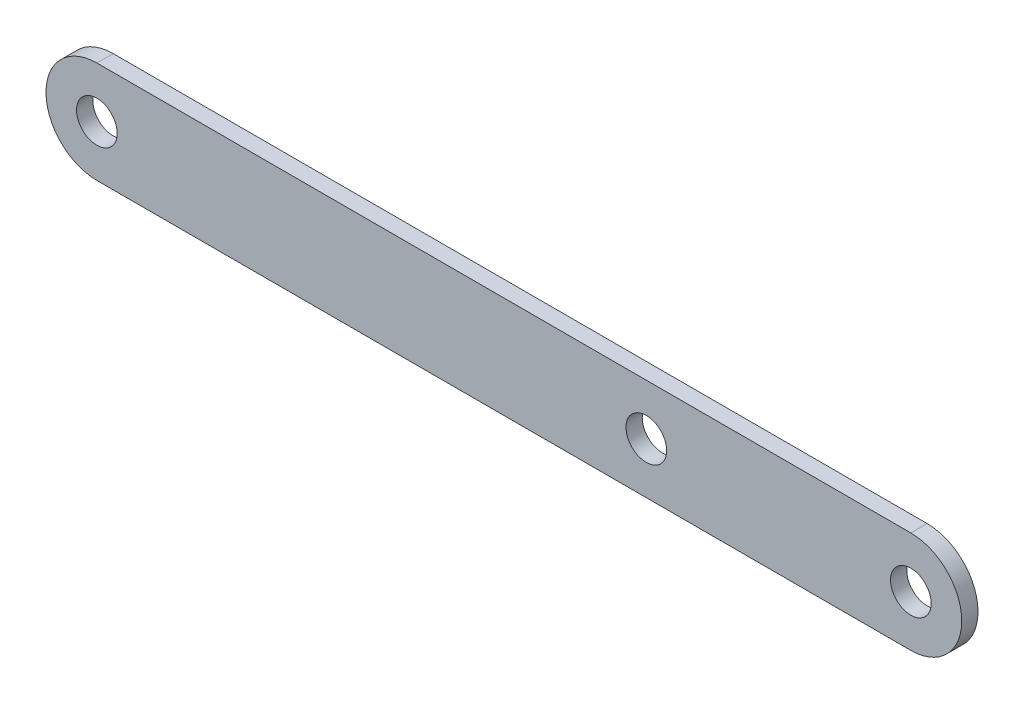
SolidWorks part; units mm, degrees
ref_plane "Plan de face" through (0, 0, 0) normal (0, 0, 1) x (1, 0, 0)
ref_plane "Plan de dessus" through (0, 0, 0) normal (0, 1, 0) x (1, 0, 0)
ref_plane "Plan de droite" through (0, 0, 0) normal (1, 0, 0) x (0, 0, -1)
sketch "Esquisse1" plane through (0, 0, 0) normal (0, 0, 1) x (1, 0, 0)
  line L0 (-200, 0) -> (200, 0) construction
  line L1 (-200, 25) -> (200, 25)
  line L2 (-200, -25) -> (200, -25)
  arc A0 (-200, 25) -> (-200, -25) centre (-200, 0) ccw
  arc A1 (200, -25) -> (200, 25) centre (200, 0) ccw
  point P2 (0, 0)
  dimension "D1" = 400
  dimension "D2" = 50
extrude "Boss.-Extru.1" add sketch "Esquisse1" along normal mid plane 8
sketch "Esquisse2" plane through (0, 0, 4) normal (0, 0, 1) x (1, 0, 0)
  circle A0 centre (-200, 0) radius 10
  circle A1 centre (200, 0) radius 10
  arc A2 (-200, 25) -> (-200, -25) centre (-200, 0) ccw construction
  arc A3 (200, -25) -> (200, 25) centre (200, 0) ccw construction
  dimension "D1" = 20
extrude "Enlèv. mat.-Extru.1" cut sketch "Esquisse2" against normal through all
sketch "Esquisse3" plane through (0, 0, -4) normal (0, 0, -1) x (-1, 0, 0)
  line L0 (200, 0) -> (-70, 0) construction
  circle A0 centre (-70, 0) radius 10
  circle A1 centre (200, 0) radius 10 construction
  dimension "D1" = 70
extrude "Enlèv. mat.-Extru.2" cut sketch "Esquisse3" against normal through all
